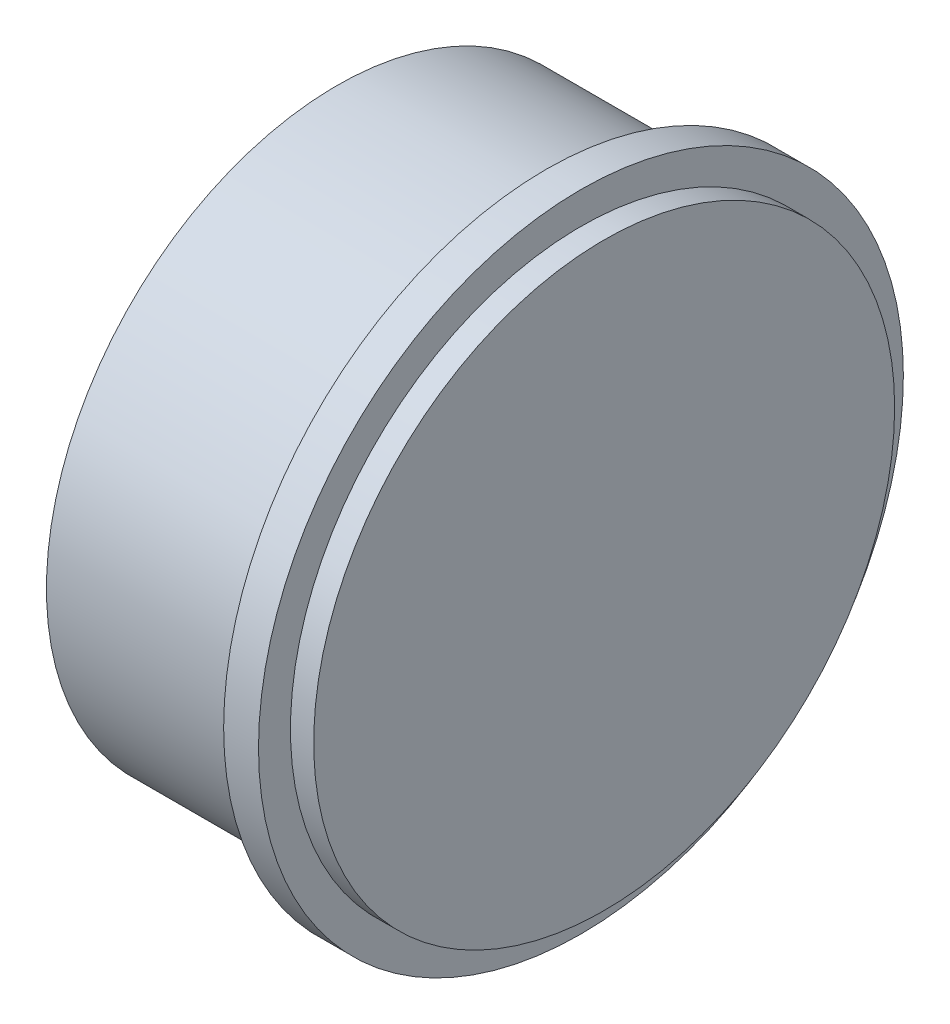
SolidWorks part; units mm, degrees
ref_plane "Front Plane" through (0, 0, 0) normal (0, 0, 1) x (1, 0, 0)
ref_plane "Top Plane" through (0, 0, 0) normal (0, 1, 0) x (1, 0, 0)
ref_plane "Right Plane" through (0, 0, 0) normal (1, 0, 0) x (0, 0, -1)
sketch "Sketch1" plane through (0, 0, 0) normal (1, 0, 0) x (0, 0, -1)
  circle A0 centre (0, 0) radius 635
extrude "Boss-Extrude1" add sketch "Sketch1" along normal blind 457.2
sketch "Sketch2" plane through (457.2, 0, 0) normal (1, 0, 0) x (0, 0, -1)
  circle A0 centre (0, 0) radius 704.85
extrude "Boss-Extrude2" add sketch "Sketch2" along normal blind 76.2
sketch "Sketch3" plane through (533.4, 0, 0) normal (1, 0, 0) x (0, 0, -1)
  circle A0 centre (0, 0) radius 635
extrude "Boss-Extrude3" add sketch "Sketch3" along normal blind 50.8
